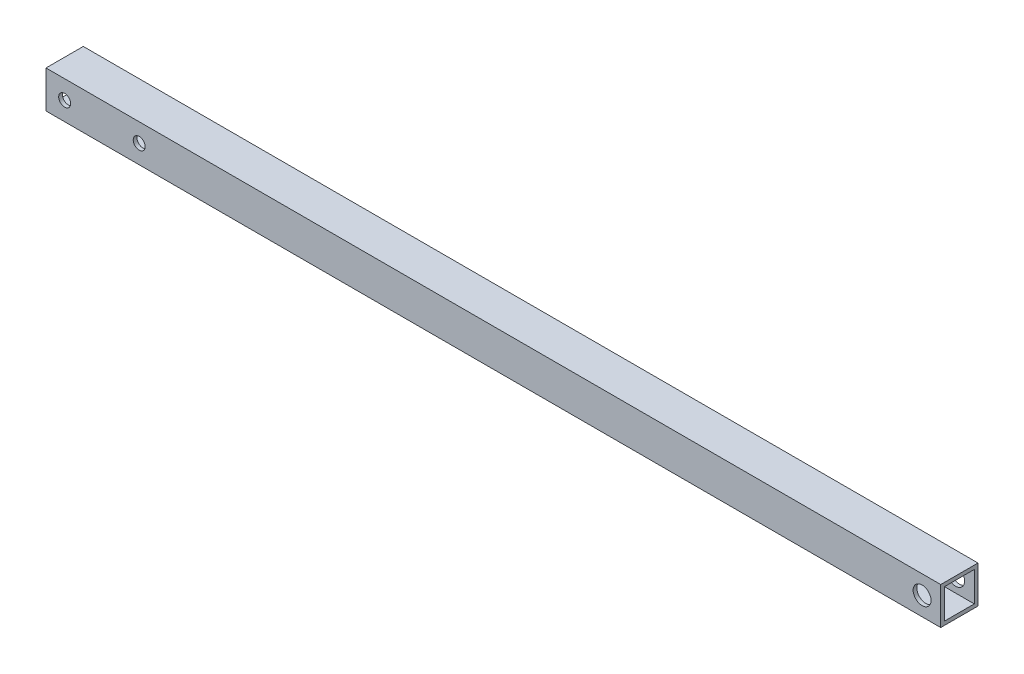
SolidWorks part; units mm, degrees
ref_plane "正面" through (0, 0, 0) normal (0, 0, 1) x (1, 0, 0)
ref_plane "平面" through (0, 0, 0) normal (0, 1, 0) x (1, 0, 0)
ref_plane "右側面" through (0, 0, 0) normal (1, 0, 0) x (0, 0, -1)
sketch "ｽｹｯﾁ1" plane through (0, 0, 0) normal (0, 0, 1) x (1, 0, 0)
  line L1 (-332.2947, 240) -> (-572.2947, 240)
  line L2 (-332.2947, 240) -> (-332.2947, 250)
  line L3 (-332.2947, 250) -> (-572.2947, 250)
  line L4 (-572.2947, 240) -> (-572.2947, 250)
  circle A1 centre (-567.2947, 245) radius 1.6
  circle A2 centre (-547.2947, 245) radius 1.6
  circle A4 centre (-337.2947, 245) radius 2.4
  dimension "D2" = 20
  dimension "D5" = 5
  dimension "D4" = 240
extrude "ﾎﾞｽ - 押し出し1" add sketch "ｽｹｯﾁ1" along normal blind 10
sketch "ｽｹｯﾁ2" plane through (-572.2947, 0, 0) normal (-1, 0, 0) x (0, 0, 1)
  line L0 (10, 240) -> (0, 240) construction
  line L1 (1, 241) -> (9, 241)
  line L2 (1, 241) -> (1, 249)
  line L3 (1, 249) -> (9, 249)
  line L4 (9, 241) -> (9, 249)
  line L5 (0, 250) -> (0, 240) construction
  dimension "D1" = 1
  dimension "D2" = 8
  dimension "D3" = 8
  dimension "D4" = 1
extrude "ｶｯﾄ - 押し出し1" cut sketch "ｽｹｯﾁ2" against normal through all
